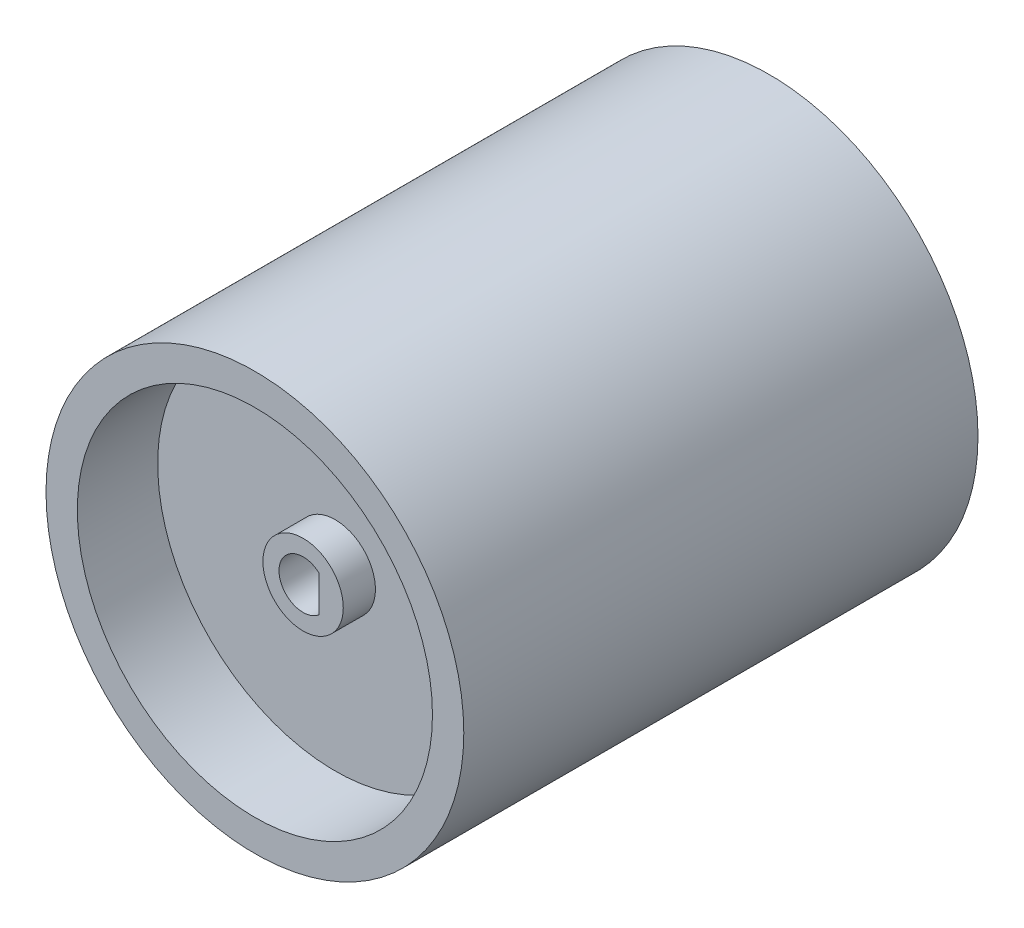
SolidWorks part; units mm, degrees
ref_plane "前视基准面" through (0, 0, 0) normal (0, 0, 1) x (1, 0, 0)
ref_plane "上视基准面" through (0, 0, 0) normal (0, 1, 0) x (1, 0, 0)
ref_plane "右视基准面" through (0, 0, 0) normal (1, 0, 0) x (0, 0, -1)
sketch "草图1" plane through (0, 0, 0) normal (0, 0, 1) x (1, 0, 0)
  circle A0 centre (0, 0) radius 11
  circle A1 centre (0, 0) radius 13
extrude "凸台-拉伸1" add sketch "草图1" along normal blind 7
sketch "草图3" plane through (0, 0, 0) normal (0, 0, -1) x (-1, 0, 0)
  circle A0 centre (0, 0) radius 13
extrude "凸台-拉伸2" add sketch "草图3" against normal blind 2
sketch "草图6" plane through (0, 0, 0) normal (0, 0, -1) x (-1, 0, 0)
  line L2 (-1, -1.118) -> (-1, 1.118)
  arc A0 (-1, -1.118) -> (-1, 1.118) centre (0, 0) ccw
extrude "切除-拉伸1" cut sketch "草图6" against normal up to next
sketch "草图7" plane through (0, 0, 2) normal (0, 0, 1) x (1, 0, 0)
  line L0 (1, -1.118) -> (1, 1.118)
  circle A0 centre (0, 0) radius 2.5
  arc A1 (1, 1.118) -> (1, -1.118) centre (0, 0) ccw
extrude "凸台-拉伸3" add sketch "草图7" along normal blind 2
sketch "草图8" plane through (0, 0, 0) normal (0, 0, -1) x (-1, 0, 0)
  circle A0 centre (0, 0) radius 11
  circle A1 centre (0, 0) radius 13
extrude "凸台-拉伸4" add sketch "草图8" along normal blind 27
sketch "草图9" plane through (0, 0, 0) normal (0, 0, -1) x (-1, 0, 0)
  line L0 (-1, -1.118) -> (-1, 1.118)
  circle A0 centre (0, 0) radius 11.5267
  arc A1 (-1, -1.118) -> (-1, 1.118) centre (0, 0) ccw
sketch "草图10" plane through (0, 0, -27) normal (0, 0, -1) x (-1, 0, 0)
  circle A0 centre (0, 0) radius 11.05
extrude "切除-拉伸2" cut sketch "草图10" against normal blind 27
sketch "草图11" plane through (0, 0, 7) normal (0, 0, 1) x (1, 0, 0)
  circle A0 centre (0, 0) radius 11.05
  circle A1 centre (0, 0) radius 2.5
extrude "切除-拉伸3" cut sketch "草图11" against normal blind 5
sketch "草图12" plane through (0, 0, -27) normal (0, 0, -1) x (-1, 0, 0)
  circle A0 centre (0, 0) radius 14.8479
extrude "切除-拉伸4" cut sketch "草图12" against normal blind 2
